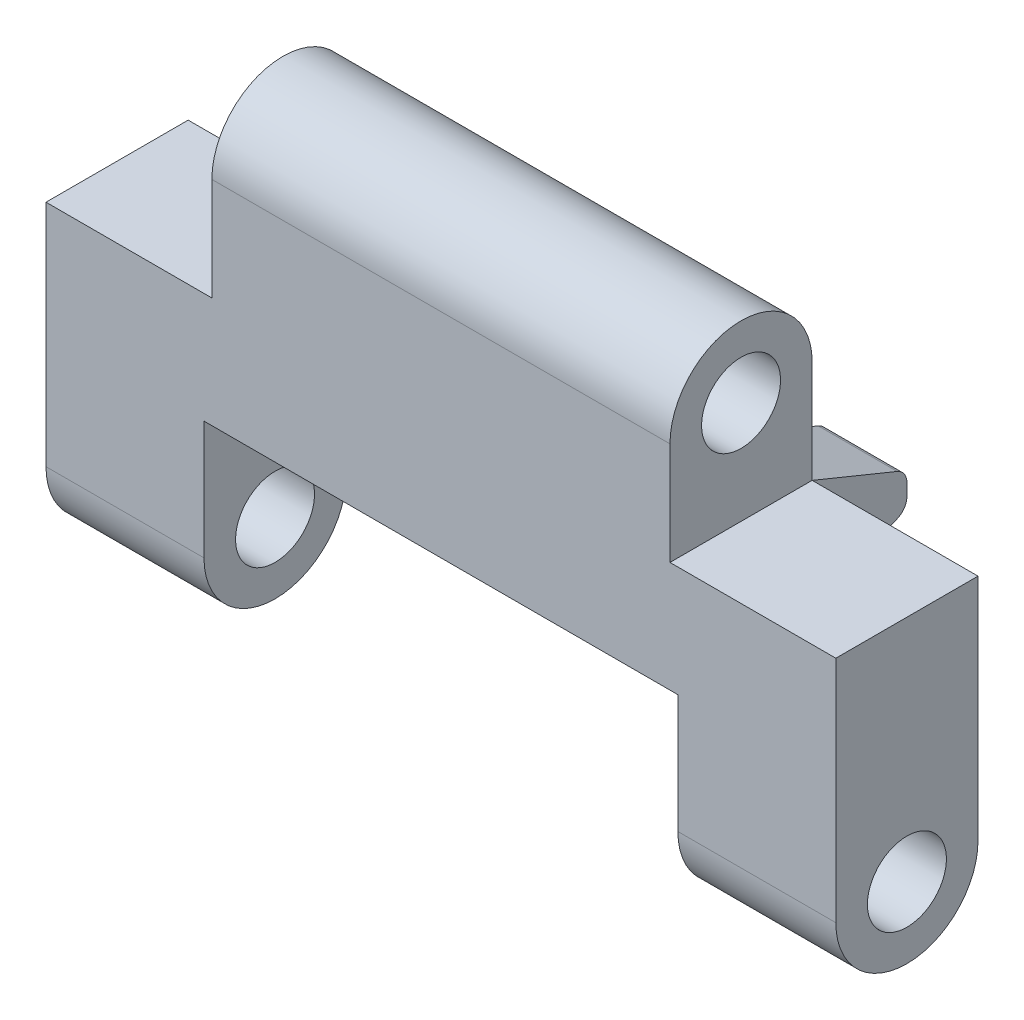
SolidWorks part; units mm, degrees
ref_plane "Front Plane" through (0, 0, 0) normal (0, 0, 1) x (1, 0, 0)
ref_plane "Top Plane" through (0, 0, 0) normal (0, 1, 0) x (1, 0, 0)
ref_plane "Right Plane" through (0, 0, 0) normal (1, 0, 0) x (0, 0, -1)
sketch "Sketch1" plane through (0, 0, 0) normal (0, 0, 1) x (1, 0, 0)
  line L0 (0, 0) -> (10.5, 0)
  line L1 (10.5, 0) -> (10.5, 11)
  line L2 (10.5, 11) -> (39.5, 11)
  line L3 (39.5, 11) -> (39.5, 0)
  line L4 (39.5, 0) -> (50, 0)
  line L5 (50, 0) -> (50, -19)
  line L6 (50, -19) -> (40, -19)
  line L7 (40, -19) -> (40, -7)
  line L8 (40, -7) -> (10, -7)
  line L9 (10, -7) -> (10, -19)
  line L10 (10, -19) -> (0, -19)
  line L11 (0, -19) -> (0, 0)
  dimension "D1" = 11
  dimension "D2" = 19
  dimension "D3" = 12
  dimension "D4" = 12
  dimension "D5" = 10
  dimension "D6" = 10
  dimension "D7" = 50
  dimension "D8" = 29
  dimension "D9" = 10.5
extrude "Boss-Extrude1" add sketch "Sketch1" along normal blind 9
sketch "Sketch2" plane through (0, 0, 0) normal (-1, 0, 0) x (0, 0, 1)
  line L0 (9, -19) -> (0, -19) construction
  line L1 (0, 0) -> (0, -19) construction
  line L2 (9, 11) -> (0, 11) construction
  line L3 (0, 11) -> (0, 0) construction
  circle A0 centre (4.5, -14.5) radius 2.5
  circle A1 centre (4.5, 6.5) radius 2.5
  dimension "D1" = 4.5
  dimension "D3" = 5
  dimension "D4" = 5
  dimension "D2" = 4.5
  dimension "D5" = 4.5
  dimension "D6" = 4.5
extrude "Cut-Extrude1" cut sketch "Sketch2" against normal blind 56
sketch "Sketch5" plane through (0, 0, 0) normal (0, 0, -1) x (-1, 0, 0)
  line L0 (-10, -7) -> (-40, -7) construction
  line L5 (-10.501, 0) -> (-15.501, 0)
  line L6 (-10.501, 0) -> (-10.501, -7)
  line L7 (-10.501, -7) -> (-15.501, -7)
  line L8 (-15.501, 0) -> (-15.501, -7)
  line L10 (-39.501, -7) -> (-34.501, -7)
  line L11 (-39.501, -7) -> (-39.501, 0)
  line L12 (-39.501, 0) -> (-34.501, 0)
  line L13 (-34.501, -7) -> (-34.501, 0)
  line L14 (-10.5, 11) -> (-10.5, 0) construction
  line L16 (-39.5, 0) -> (-39.5, 11) construction
  dimension "D1" = 5
  dimension "D2" = 0.001
  dimension "D3" = 5
  dimension "D4" = 0.001
  dimension "D5" = 7
  dimension "D6" = 7
extrude "Boss-Extrude2" add sketch "Sketch5" along normal blind 6
sketch "Sketch6" plane through (39.501, 0, 0) normal (1, 0, 0) x (0, 0, -1)
  line L0 (0, -7) -> (5.3786, -4.8)
  line L1 (6, 0) -> (6, -7) construction
  line L2 (6, -3.8744) -> (6, -3.1256)
  line L3 (5.3786, -2.2) -> (0, 0)
  line L4 (0, 0) -> (0, 0.7111)
  line L5 (0, 0.7111) -> (7.3827, 0.7111)
  line L6 (7.3827, 0.7111) -> (7.3827, -8.4334)
  line L7 (7.3827, -8.4334) -> (0, -8.4334)
  line L8 (0, -19) -> (0, 0) construction
  line L9 (0, -8.4334) -> (0, -7)
  line L10 (6, -7) -> (0, -7) construction
  line L11 (6, 0) -> (0, 0) construction
  arc A0 (6, -3.1256) -> (5.3786, -2.2) centre (5, -3.1256) ccw
  arc A1 (5.3786, -4.8) -> (6, -3.8744) centre (5, -3.8744) ccw
  point P17 (6, -2.4542)
  point P20 (6, -4.5458)
  dimension "D1" = 1
  dimension "D2" = 2.2
  dimension "D3" = 2.2
extrude "Cut-Extrude3" cut sketch "Sketch6" against normal blind 30
sketch "Sketch7" plane through (50, 0, 0) normal (1, 0, 0) x (0, 0, -1)
  line L0 (0, 6.5) -> (1.7283, 6.5)
  line L1 (1.7283, 6.5) -> (1.7283, 12.3137)
  line L2 (1.7283, 12.3137) -> (-10.4932, 12.3137)
  line L3 (-10.4932, 12.3137) -> (-10.4932, 4.7426)
  line L4 (-9, 6.5) -> (-10.4932, 4.7426)
  line L5 (0, -14.5) -> (1.2287, -14.5)
  line L6 (1.2287, -14.5) -> (1.2287, -21.1223)
  line L7 (1.2287, -21.1223) -> (-10.4932, -21.1223)
  line L8 (-9, -14.5) -> (-10.4932, -14.5)
  line L9 (-10.4932, -14.5) -> (-10.4932, -21.1223)
  arc A0 (-9, -14.5) -> (0, -14.5) centre (-4.5, -14.5) ccw
  arc A1 (0, 6.5) -> (-9, 6.5) centre (-4.5, 6.5) ccw
extrude "Cut-Extrude4" cut sketch "Sketch7" against normal blind 60
